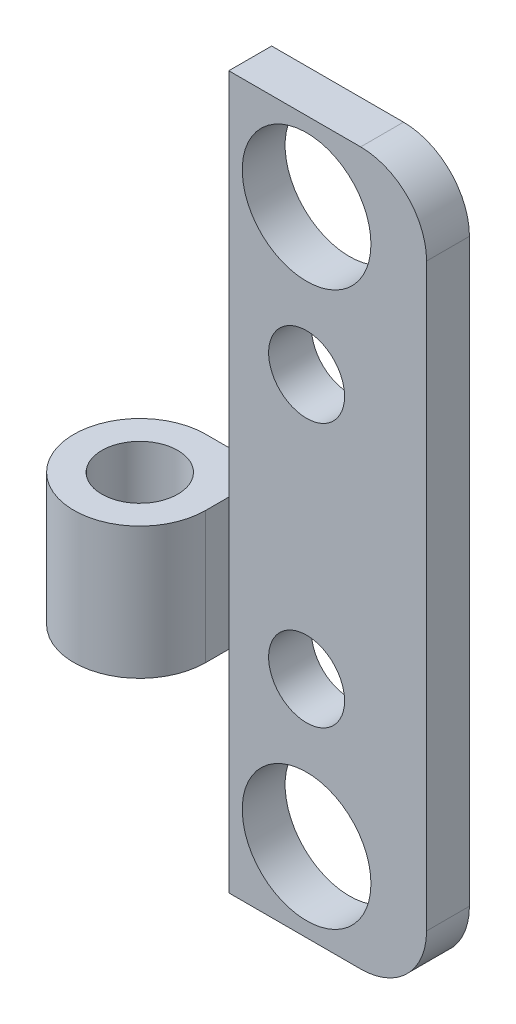
SolidWorks part; units mm, degrees
ref_plane "Front Plane" through (0, 0, 0) normal (0, 0, 1) x (1, 0, 0)
ref_plane "Top Plane" through (0, 0, 0) normal (0, 1, 0) x (1, 0, 0)
ref_plane "Right Plane" through (0, 0, 0) normal (1, 0, 0) x (0, 0, -1)
sketch "Sketch1" plane through (0, 0, 0) normal (0, 0, 1) x (1, 0, 0)
  line L0 (7.493, 46.99) -> (7.493, 54.61) construction
  line L1 (0, 0) -> (12.7, 0)
  line L2 (0, 0) -> (0, 68.58)
  line L3 (0, 68.58) -> (12.7, 68.58)
  line L4 (19.05, 6.35) -> (19.05, 62.23)
  line L5 (7.493, 46.99) -> (7.493, 21.59) construction
  line L6 (7.493, 34.29) -> (0, 34.29) construction
  circle A0 centre (7.493, 46.99) radius 3.6576 construction
  circle A1 centre (7.493, 21.59) radius 3.6576 construction
  circle A2 centre (7.493, 60.96) radius 3.6576 construction
  circle A3 centre (7.493, 7.62) radius 3.6576 construction
  arc A4 (12.7, 0) -> (19.05, 6.35) centre (12.7, 6.35) ccw
  arc A5 (19.05, 62.23) -> (12.7, 68.58) centre (12.7, 62.23) ccw
  circle A6 centre (7.493, 46.99) radius 6.1976 construction
  circle A7 centre (7.493, 21.59) radius 6.1976 construction
  circle A8 centre (7.493, 60.96) radius 6.1976
  circle A9 centre (7.493, 7.62) radius 6.1976
  point P16 (19.05, 0)
  dimension "D4" = 7.493
  dimension "D6" = 6.35
  dimension "D7" = 7.3152
  dimension "D9" = 7.62
  dimension "D10" = 12.3952
  dimension "D1" = 19.05
  dimension "D2" = 68.58
  dimension "D3" = 7.62
  dimension "D5" = 25.4
  dimension "D8" = 7.62
extrude "Boss-Extrude1" add sketch "Sketch1" along normal blind 4.1275
sketch "Sketch2" plane through (0, 68.58, 0) normal (0, 1, 0) x (1, 0, 0)
  line L0 (0, 0) -> (-6.35, 0)
  line L2 (0, -6.35) -> (0, -4.1275)
  line L3 (0, -4.1275) -> (0, 0)
  circle A0 centre (-6.35, -6.35) radius 3.6576
  arc A2 (-6.35, 0) -> (0, -6.35) centre (-6.35, -6.35) ccw
  point P6 (-20.32, 0)
  dimension "D2" = 7.3152
  dimension "D1" = 6.35
extrude "Boss-Extrude2" add sketch "Sketch2" against normal blind 12.7 from offset 35.56 offset against normal yes
sketch "Sketch3" plane through (0, 0, 4.1275) normal (0, 0, 1) x (1, 0, 0)
  line L0 (0, 20.32) -> (0, 0) construction
  line L1 (7.493, 46.99) -> (7.493, 21.59) construction
  line L2 (7.493, 34.29) -> (19.05, 34.29) construction
  line L3 (19.05, 6.35) -> (19.05, 62.23) construction
  circle A0 centre (7.493, 46.99) radius 6.1976 construction
  circle A1 centre (7.493, 21.59) radius 6.1976 construction
  circle A2 centre (7.493, 46.99) radius 3.6576
  circle A3 centre (7.493, 21.59) radius 3.6576
  dimension "D1" = 12.3952
  dimension "D2" = 7.493
  dimension "D3" = 7.493
  dimension "D4" = 25.4
extrude "Cut-Extrude1" cut sketch "Sketch3" against normal through all
sketch "Sketch4" plane through (0, 0, 4.1275) normal (0, 0, 1) x (1, 0, 0)
  line L0 (19.05, 34.29) -> (-14.5896, 34.29) construction
  line L1 (19.05, 6.35) -> (19.05, 62.23) construction
  line L2 (-12.7, 20.32) -> (0, 20.32) construction
  dimension "D1" = 13.97
